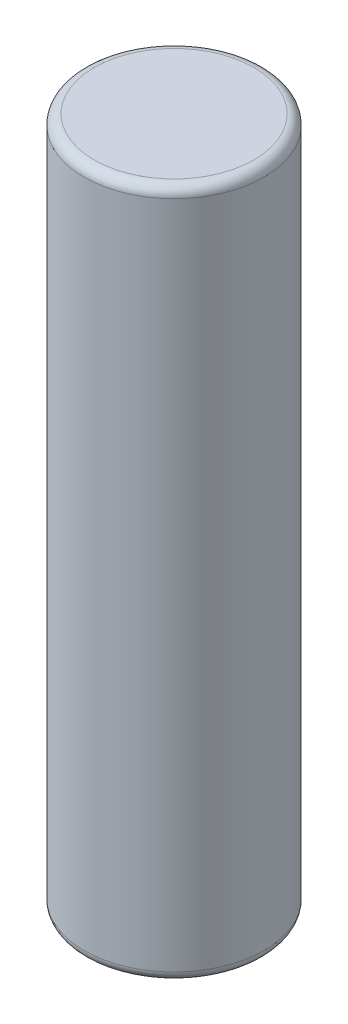
SolidWorks part; units mm, degrees
material "1060-H18 Rod (SS)"
ref_plane "Front Plane" through (0, 0, 0) normal (0, 0, 1) x (1, 0, 0)
ref_plane "Top Plane" through (0, 0, 0) normal (0, 1, 0) x (1, 0, 0)
ref_plane "Right Plane" through (0, 0, 0) normal (1, 0, 0) x (0, 0, -1)
sketch "Sketch1" plane through (0, 0, 0) normal (0, 1, 0) x (1, 0, 0)
  circle A0 centre (0, 0) radius 9
  dimension "D1" = 18
extrude "Boss-Extrude1" add sketch "Sketch1" along normal blind 69
fillet "Fillet1" radius 1 2 edges at (0, 0, 9) (0, 69, 9)
